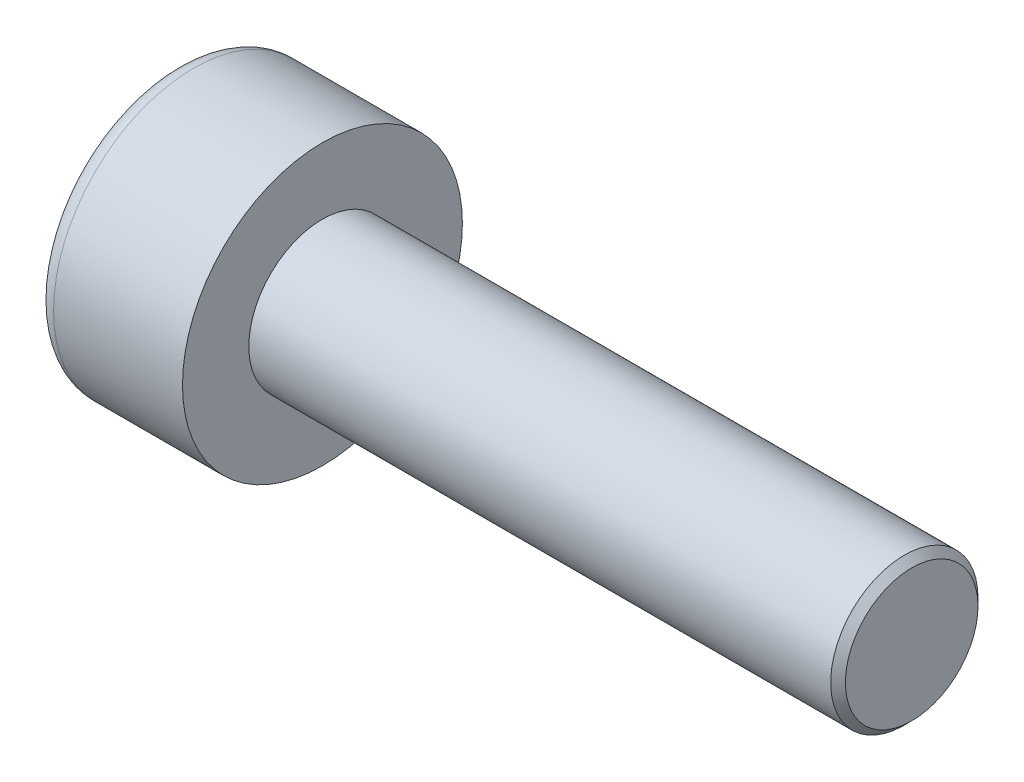
SolidWorks part; units mm, degrees
ref_plane "Front" through (0, 0, 0) normal (0, 0, 1) x (1, 0, 0)
ref_plane "Top" through (0, 0, 0) normal (0, 1, 0) x (1, 0, 0)
ref_plane "Right" through (0, 0, 0) normal (1, 0, 0) x (0, 0, -1)
sketch "Sketch1" plane through (0, 0, 0) normal (1, 0, 0) x (0, 0, -1)
  circle A0 centre (0, 0) radius 1.9
  dimension "dk" = 3.8
extrude "BaseHead" add sketch "Sketch1" along normal blind 2
sketch "Sketch2" plane through (2, 0, 0) normal (1, 0, 0) x (0, 0, -1)
  circle A0 centre (0, 0) radius 1
extrude "BaseBody" add sketch "Sketch2" along normal blind 8
cosmetic thread "ThreadCosmetic1" parameters "b"=8, "D2"=1.567
sketch "Sketch3" plane through (0, 0, 0) normal (1, 0, 0) x (0, 0, -1)
  line L1 (0.866, 0) -> (0.433, 0.75)
  line L2 (0.433, 0.75) -> (-0.433, 0.75)
  line L3 (-0.433, 0.75) -> (-0.866, 0)
  line L4 (-0.866, 0) -> (-0.433, -0.75)
  line L5 (-0.433, -0.75) -> (0.433, -0.75)
  line L6 (0.433, -0.75) -> (0.866, 0)
  circle A0 centre (0, 0) radius 0.75 construction
  dimension "s" = 1.5
  dimension "e" = 1.7321
extrude "HexagonSocket" cut sketch "Sketch3" along normal blind 1
sketch "Sketch4" plane through (-4.1961, 0.75, 0) normal (0, 0, 1) x (-1, 0, 0)
  line L0 (-5.1961, 1.5) -> (-5.6292, 0.75)
  line L2 (-5.6292, 0.75) -> (-5.1961, 0.75)
  line L3 (-5.1961, 0.75) -> (-5.1961, 1.5)
  line L4 (-5.0351, 0.75) -> (0.839, 0.75) construction
  line L5 (-14.1961, 0.75) -> (-6.1961, 0.75) construction
  line L6 (-6.1961, 0.75) -> (-4.1961, 0.75) construction
  dimension "m" = 60
revolve "Cut-Revolve1" cut sketch "Sketch4" angle 360 about L4
fillet "HeadFillet" [suppressed] radius 0.1
fillet "TopFillet" radius 0.25 1 edges at (0, 0, -1.9)
chamfer "Chamfer1" distance 0.1 angle 45 1 edges at (10, 0, -1)
sketch "Sketch5" plane through (0, 0, 0) normal (0, 0, 1) x (1, 0, 0)
  line L0 (9.9, 0.8125) -> (10.0083, 1)
  line L1 (10.0083, 1) -> (10.0083, 1.2165)
  line L2 (10.0083, 1.2165) -> (9.7917, 1.2165)
  line L3 (9.7917, 1.2165) -> (9.7917, 1)
  line L4 (9.7917, 1) -> (9.9, 0.8125)
  line L5 (0, 0) -> (7.8886, 0) construction
  line L6 (9.9, -1) -> (9.9, 1) construction
revolve "Cut-Revolve10" [suppressed] cut sketch "Sketch5" angle 360 about L5
pattern_linear "LPattern10" [suppressed] count 31 spacing 0.2598 along (1, 0, 0)
equation "\"r1@TopFillet\" = \"d@Sketch2\" / 8"
equation "\"D1@Chamfer1\" = \"r@HeadFillet\""
equation "\"D1@Sketch5\" = \"d@Sketch2\""
equation "\"D2@Sketch5\" =  ( \"d@Sketch2\" - \"D2@ThreadCosmetic1\" )  / 2"
equation "\"D3@LPattern10\" = \"D2@Sketch5\" * 1.2"
equation "\"D1@LPattern10\" = \"b@ThreadCosmetic1\" / \"D3@LPattern10\""
